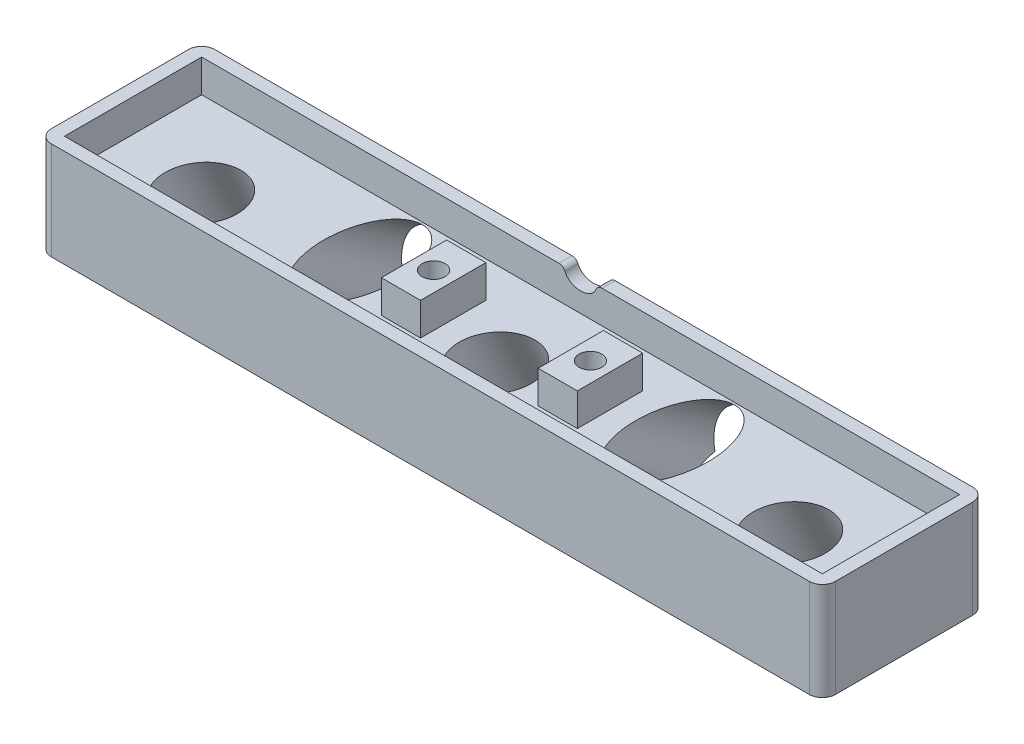
SolidWorks part; units mm, degrees
ref_plane "Front Plane" through (0, 0, 0) normal (0, 0, 1) x (1, 0, 0)
ref_plane "Top Plane" through (0, 0, 0) normal (0, 1, 0) x (1, 0, 0)
ref_plane "Right Plane" through (0, 0, 0) normal (1, 0, 0) x (0, 0, -1)
sketch "Base" plane through (0, 0, 0) normal (0, 1, 0) x (1, 0, 0)
  line L1 (60, -12.5) -> (-60, -12.5)
  line L2 (60, -12.5) -> (60, 12.5)
  line L3 (60, 12.5) -> (-60, 12.5)
  line L4 (-60, -12.5) -> (-60, 12.5)
  line L5 (60, -12.5) -> (-60, 12.5) construction
  line L6 (60, 12.5) -> (-60, -12.5) construction
  point P0 (0, 0)
  dimension "D1" = 25
  dimension "D2" = 120
extrude "Base EXT" add sketch "Base" along normal blind 10
ref_plane "3 LEDs - bottom" through (0, 13.0017, 6.0628) normal (0, 0.9063, 0.4226) x (1, 0, 0)
sketch "Sketch3" plane through (0, 13.0017, 6.0628) normal (0, 0.9063, 0.4226) x (1, 0, 0)
  line L0 (-60, 15.555) -> (-60, -7.1027) construction
  line L1 (60, -7.1027) -> (60, 15.555) construction
  line L2 (-45, 1.8973) -> (45, 1.8973) construction
  line L3 (0, 1.8973) -> (0, 16.1716) construction
  line L4 (-60, -7.1027) -> (60, -7.1027) construction
  circle A0 centre (-45, 1.8973) radius 5.5
  circle A1 centre (0, 1.8973) radius 5.5
  circle A2 centre (45, 1.8973) radius 5.5
  point P6 (-60, 4.2262)
  dimension "D1" = 11
  dimension "D2" = 15
  dimension "D3" = 15
  dimension "D4" = 9
extrude "LED bottom CUT" cut sketch "Sketch3" against normal through all
ref_plane "2 LED - top" through (0, 9.163, 13.0861) normal (0, 0.5736, 0.8192) x (1, 0, 0)
sketch "LED for Top Row" plane through (0, 9.163, 13.0861) normal (0, 0.5736, 0.8192) x (1, 0, 0)
  line L0 (-60, 1.0218) -> (60, 1.0218) construction
  line L1 (-46.4033, 9.1543) -> (-1.4033, 9.1543) construction
  line L2 (-23.9033, 9.1543) -> (-23.9033, 17.585) construction
  line L3 (0, 1.0218) -> (0, 20.7951) construction
  circle A0 centre (-23.9033, 8.5218) radius 5.5
  circle A1 centre (23.9033, 8.5218) radius 5.5
  dimension "D1" = 11
  dimension "D2" = 7.5
extrude "LED top CUT" cut sketch "LED for Top Row" against normal through all
sketch "Sketch5" plane through (0, 10, 0) normal (0, 1, 0) x (1, 0, 0)
  line L0 (-60, 12.5) -> (60, 12.5)
  line L1 (60, 12.5) -> (60, -12.5)
  line L2 (60, -12.5) -> (-60, -12.5)
  line L3 (-60, -12.5) -> (-60, 12.5)
  line L4 (-58, 10.5) -> (58, 10.5)
  line L5 (58, 10.5) -> (58, -10.5)
  line L6 (58, -10.5) -> (-58, -10.5)
  line L7 (-58, -10.5) -> (-58, 10.5)
  dimension "D1" = 2
  dimension "D2" = 2
  dimension "D3" = 2
  dimension "D5" = 2
extrude "Wire Box Rim" add sketch "Sketch5" along normal blind 5
sketch "Sketch6" plane through (0, 10, 0) normal (0, 1, 0) x (1, 0, 0)
  line L0 (-58, 0) -> (58, 0) construction
  line L1 (-15, 5) -> (-9, 5)
  line L2 (-15, 5) -> (-15, -5)
  line L3 (-15, -5) -> (-9, -5)
  line L4 (-9, 5) -> (-9, -5)
  line L5 (-58, 10.5) -> (-58, -10.5) construction
  line L6 (58, -10.5) -> (58, 10.5) construction
  line L7 (0, 0) -> (0, -5) construction
  line L8 (9, 5) -> (9, -5)
  line L9 (15, -5) -> (9, -5)
  line L10 (15, 5) -> (15, -5)
  line L11 (15, 5) -> (9, 5)
  line L12 (-12, 5) -> (-12, 1.7184) construction
  dimension "D1" = 6
  dimension "D2" = 10
  dimension "D3" = 5
  dimension "D4" = 12
extrude "Support Spacers" add sketch "Sketch6" along normal up to surface (5 mm away) up to face at (0, 15, 0)
sketch "Sketch8" plane through (0, 15, 0) normal (0, 1, 0) x (1, 0, 0)
  line L0 (12, -5) -> (12, 5) construction
  line L1 (15, -5) -> (9, -5) construction
  line L2 (9, 5) -> (15, 5) construction
  line L3 (12, 0) -> (13.7942, 0) construction
  line L6 (0, -10.5) -> (0, -3.6056) construction
  line L7 (-58, -10.5) -> (58, -10.5) construction
  circle A0 centre (12, 0) radius 1.75
  circle A1 centre (-12, 0) radius 1.75
  dimension "D1" = 3.5
extrude "M3 Screw CUT" cut sketch "Sketch8" against normal through all
sketch "Wire cut out" plane through (0, 0, -12.5) normal (0, 0, -1) x (-1, 0, 0)
  line L1 (-60, 15) -> (60, 15) construction
  ellipse E0 centre (0, 15) end of major axis (-2.5, 15) minor radius 2
  dimension "D1" = 2
  dimension "D2" = 5
extrude "Wire cut out CUT" cut sketch "Wire cut out" against normal up to surface (2 mm away) up to face at (0, 12.5, -10.5)
fillet "Fillet1" radius 1 3 edges at (0, 13, -12.5) (0, 13, -10.5) (2.5, 15, -11.5)
fillet "Fillet2" radius 1 1 edges at (-2.5, 15, -11.5)
fillet "Fillet3" radius 2 1 edges at (-60, 7.5, -12.5)
fillet "Fillet4" radius 2 1 edges at (60, 7.5, -12.5)
fillet "Fillet5" radius 2 1 edges at (60, 7.5, 12.5)
fillet "Fillet6" radius 2 1 edges at (-60, 7.5, 12.5)
sketch "M3 Nut" plane through (0, 0, 0) normal (0, -1, 0) x (1, 0, 0)
  line L0 (-12, 0) -> (-12, 5.4712) construction
  line L1 (-12, 3.1754) -> (-14.75, 1.5877)
  line L2 (-14.75, 1.5877) -> (-14.75, -1.5877)
  line L3 (-14.75, -1.5877) -> (-12, -3.1754)
  line L4 (-12, -3.1754) -> (-9.25, -1.5877)
  line L5 (-9.25, -1.5877) -> (-9.25, 1.5877)
  line L6 (-9.25, 1.5877) -> (-12, 3.1754)
  line L7 (0, 12.5) -> (0, 6.2927) construction
  line L8 (-58, 12.5) -> (58, 12.5) construction
  line L9 (9.25, 1.5877) -> (12, 3.1754)
  line L10 (9.25, -1.5877) -> (9.25, 1.5877)
  line L11 (12, -3.1754) -> (9.25, -1.5877)
  line L12 (14.75, -1.5877) -> (12, -3.1754)
  line L13 (14.75, 1.5877) -> (14.75, -1.5877)
  line L14 (12, 3.1754) -> (14.75, 1.5877)
  circle A0 centre (-12, 0) radius 2.75 construction
  circle A1 centre (12, 0) radius 2.75 construction
  dimension "D1" = 5.5
extrude "Cut-Extrude5" cut sketch "M3 Nut" against normal blind 3.5
equation "\"LED_DIA\"=11"
equation "\"D1@LED for Top Row\"=\"LED_DIA\""
equation "\"D1@Sketch3\"=\"LED_DIA\""
equation "\"WIRE_BOX_WALL\"=2"
equation "\"D1@Sketch5\"=\"WIRE_BOX_WALL\""
equation "\"D2@Sketch5\"=\"WIRE_BOX_WALL\""
equation "\"D3@Sketch5\"=\"WIRE_BOX_WALL\""
equation "\"D5@Sketch5\"=\"WIRE_BOX_WALL\""
